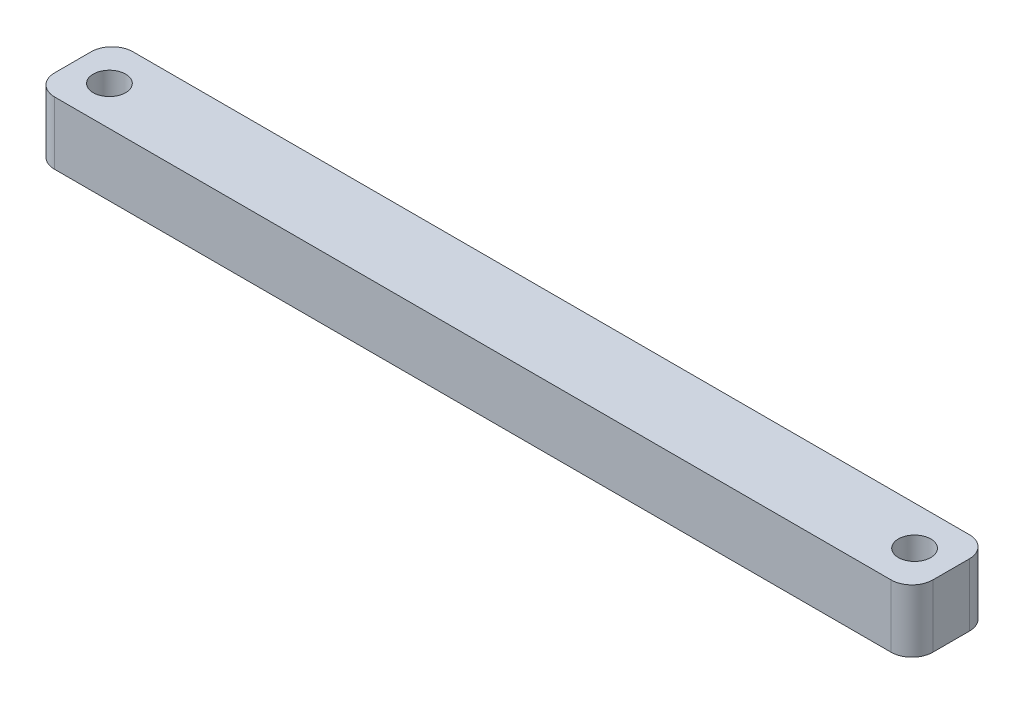
SolidWorks part; units mm, degrees
material "ABS"
ref_plane "Front Plane" through (0, 0, 0) normal (0, 0, 1) x (1, 0, 0)
ref_plane "Top Plane" through (0, 0, 0) normal (0, 1, 0) x (1, 0, 0)
ref_plane "Right Plane" through (0, 0, 0) normal (1, 0, 0) x (0, 0, -1)
sketch "Sketch1" plane through (0, 0, 0) normal (0, 1, 0) x (1, 0, 0)
  line L0 (0, 2.5) -> (0, -2.5) construction
  line L1 (-42.045, -3.75) -> (42.045, -3.75)
  line L2 (-42.045, -3.75) -> (-42.045, 3.75)
  line L3 (-42.045, 3.75) -> (42.045, 3.75)
  line L4 (42.045, -3.75) -> (42.045, 3.75)
  line L5 (-42.045, -3.75) -> (42.045, 3.75) construction
  line L6 (-42.045, 3.75) -> (42.045, -3.75) construction
  circle A1 centre (-38.545, 0) radius 1.55
  circle A3 centre (38.545, 0) radius 1.55
  point P0 (0, 0)
  dimension "D3" = 3.5
  dimension "D4" = 3.1
  dimension "D6" = 3.5
  dimension "D2" = 7.5
  dimension "D5" = 3.75
  dimension "D7" = 77.09
extrude "Boss-Extrude1" add sketch "Sketch1" along normal blind 6
fillet "Fillet5" radius 2 4 edges at (42.045, 3, -3.75) (42.045, 3, 3.75) (-42.045, 3, -3.75) (-42.045, 3, 3.75)
